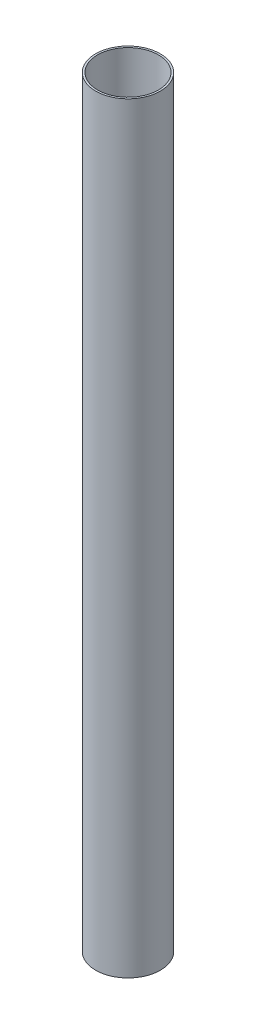
SolidWorks part; units mm, degrees
ref_plane "前视基准面" through (0, 0, 0) normal (0, 0, 1) x (1, 0, 0)
ref_plane "上视基准面" through (0, 0, 0) normal (0, 1, 0) x (1, 0, 0)
ref_plane "右视基准面" through (0, 0, 0) normal (1, 0, 0) x (0, 0, -1)
other "Configuration Table"
sketch "草图1" plane through (0, 0, 0) normal (0, 1, 0) x (1, 0, 0)
  circle A0 centre (0, 0) radius 8
  circle A1 centre (0, 0) radius 8.5
  dimension "D1" = 16
  dimension "D2" = 17
extrude "凸台-拉伸1" add sketch "草图1" along normal blind 200
